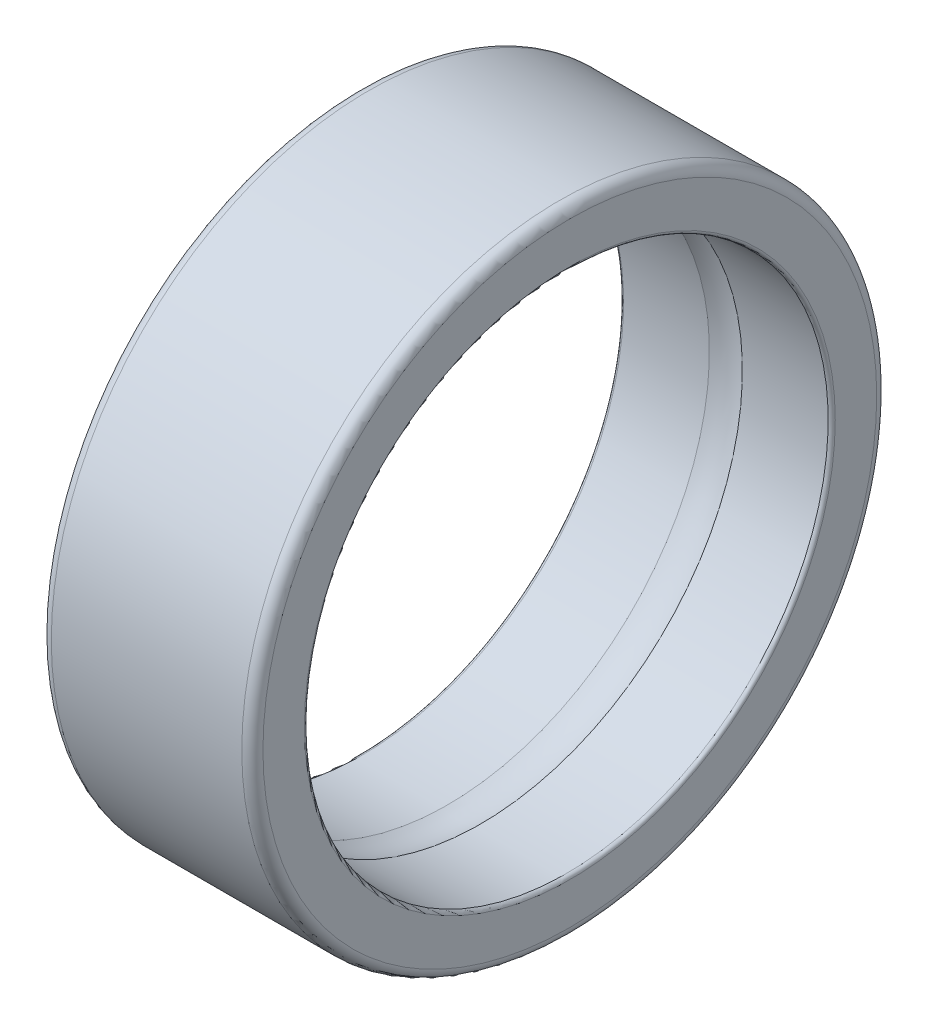
SolidWorks part; units mm, degrees
ref_plane "Ebene vorne" through (0, 0, 0) normal (0, 0, 1) x (1, 0, 0)
ref_plane "Ebene oben" through (0, 0, 0) normal (0, 1, 0) x (1, 0, 0)
ref_plane "Ebene rechts" through (0, 0, 0) normal (1, 0, 0) x (0, 0, -1)
ref_plane "Plane1" through (0, 0, 0) normal (0, 0, 1) x (1, 0, 0)
sketch "Sketch1" plane through (0, 0, 0) normal (0, 0, 1) x (1, 0, 0)
  line L0 (0.0667, 4.95) -> (1.6878, 4.95)
  line L1 (2.3122, 4.95) -> (3.9333, 4.95)
  line L2 (4, 5.0167) -> (4, 5.8)
  line L3 (3.8, 6) -> (0.2, 6)
  line L4 (0, 5.8) -> (0, 5.0167)
  line L5 (4, 0) -> (-4, 0) construction
  arc A0 (0, 5.0167) -> (0.0667, 4.95) centre (0.0667, 5.0167) ccw
  arc A1 (1.6878, 4.95) -> (2.3122, 4.95) centre (2, 4) cw
  arc A2 (3.9333, 4.95) -> (4, 5.0167) centre (3.9333, 5.0167) ccw
  arc A3 (4, 5.8) -> (3.8, 6) centre (3.8, 5.8) ccw
  arc A4 (0.2, 6) -> (0, 5.8) centre (0.2, 5.8) ccw
revolve "Revolve1" add sketch "Sketch1" angle 360 about L5
